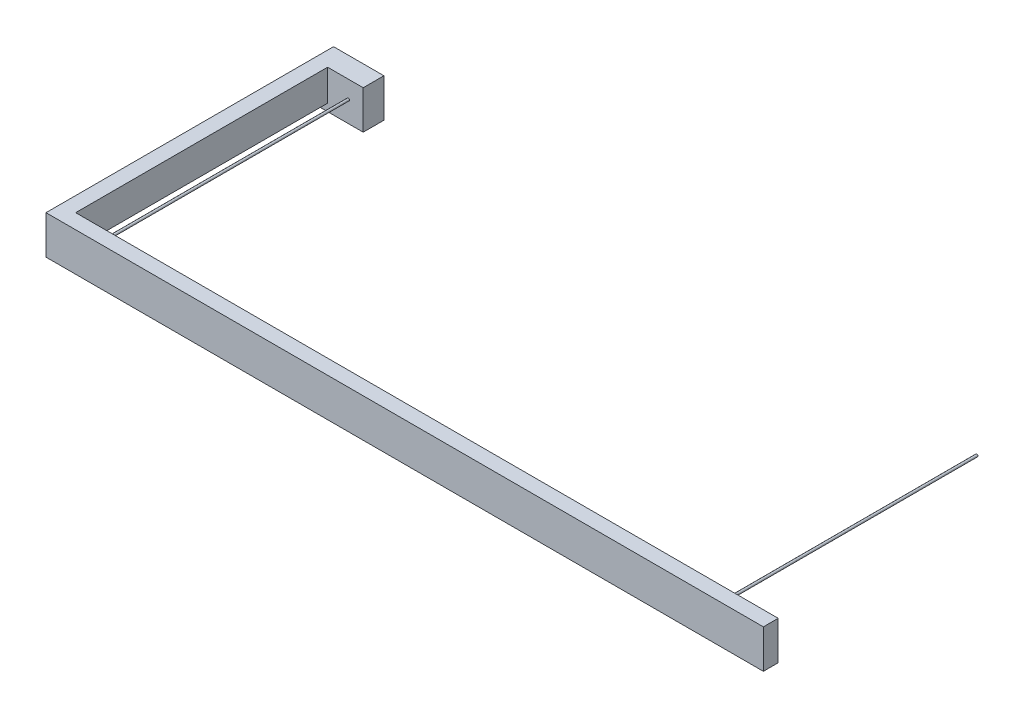
SolidWorks part; units mm, degrees
ref_plane "Front Plane" through (0, 0, 0) normal (0, 0, 1) x (1, 0, 0)
ref_plane "Top Plane" through (0, 0, 0) normal (0, 1, 0) x (1, 0, 0)
ref_plane "Right Plane" through (0, 0, 0) normal (1, 0, 0) x (0, 0, -1)
sketch "Sketch1" plane through (0, 0, 0) normal (0, 0, 1) x (1, 0, 0)
  line L1 (0, 0) -> (25, 0)
  line L2 (0, 0) -> (0, 13)
  line L3 (0, 13) -> (25, 13)
  line L4 (25, 0) -> (25, 13)
  dimension "D1" = 13
  dimension "D2" = 25
extrude "Boss-Extrude1" add sketch "Sketch1" along normal blind 5
sketch "Sketch2" plane through (0, 0, 0) normal (0, 0, -1) x (-1, 0, 0)
  line L0 (0, 0) -> (-25, 0) construction
  line L2 (0, 13) -> (0, 0) construction
  circle A0 centre (-5, 7.1) radius 0.4
  dimension "D1" = 0.8
  dimension "D2" = 7.1
  dimension "D3" = 5
extrude "Boss-Extrude2" add sketch "Sketch2" along normal blind 87
sketch "Sketch3" plane through (0, 0, 0) normal (-1, 0, 0) x (0, 0, 1)
  line L1 (0, 13) -> (5, 13)
  line L2 (0, 13) -> (0, 0)
  line L3 (0, 0) -> (5, 0)
  line L4 (5, 13) -> (5, 0)
extrude "Boss-Extrude3" add sketch "Sketch3" along normal blind 210
sketch "Sketch4" plane through (0, 0, 0) normal (0, 0, -1) x (-1, 0, 0)
  line L0 (210, 0) -> (-25, 0) construction
  circle A0 centre (205, 7.1) radius 0.4
  point P2 (0, 0)
  dimension "D1" = 0.8
  dimension "D2" = 7.1
  dimension "D3" = 210
extrude "Boss-Extrude4" add sketch "Sketch4" along normal blind 87
sketch "Sketch5" plane through (-210, 0, 0) normal (-1, 0, 0) x (0, 0, 1)
  line L1 (0, 13) -> (5, 13)
  line L2 (0, 13) -> (0, 0)
  line L3 (0, 0) -> (5, 0)
  line L4 (5, 13) -> (5, 0)
extrude "Boss-Extrude5" add sketch "Sketch5" along normal blind 7
sketch "Sketch6" plane through (0, 0, 0) normal (0, 0, -1) x (-1, 0, 0)
  line L0 (217, 0) -> (-25, 0) construction
  line L1 (217, 13) -> (212, 13)
  line L2 (217, 13) -> (217, 0)
  line L3 (217, 0) -> (212, 0)
  line L4 (212, 13) -> (212, 0)
  dimension "D1" = 5
extrude "Boss-Extrude6" add sketch "Sketch6" along normal blind 92
sketch "Sketch8" plane through (0, 0, 0) normal (0, -1, 0) x (1, 0, 0)
  line L1 (-212, -92) -> (-200, -92)
  line L2 (-212, -92) -> (-212, -85)
  line L3 (-212, -85) -> (-200, -85)
  line L4 (-200, -92) -> (-200, -85)
  dimension "D1" = 7
  dimension "D2" = 12
extrude "Boss-Extrude7" add sketch "Sketch8" against normal up to surface (13 mm away)
sketch "Sketch12" plane through (0, 0, 0) normal (0, 0, -1) x (-1, 0, 0)
  line L0 (204.3655, 0) -> (217, 4.113)
  line L1 (217, 0) -> (217, 13) construction
  line L2 (217, 4.113) -> (217, 0)
  line L7 (200, 0) -> (217, 0) construction
  line L8 (217, 0) -> (204.3655, 0)
extrude "Cut-Extrude4" cut sketch "Sketch12" along normal up to surface (85 mm away) up to face at (-206, 6.5, -85)
